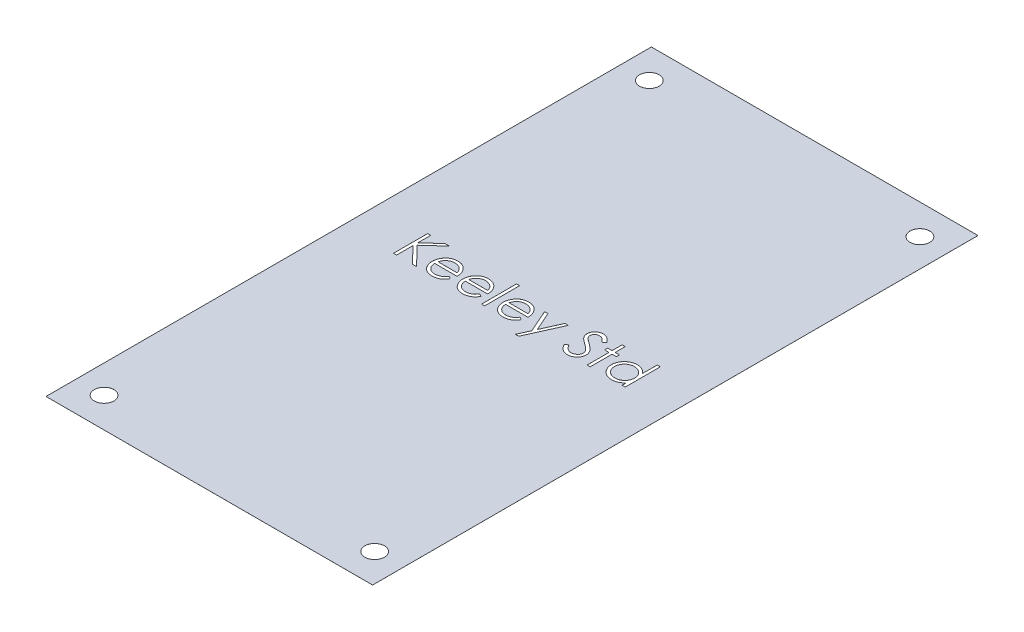
SolidWorks part; units mm, degrees
ref_plane "Front Plane" through (0, 0, 0) normal (0, 0, 1) x (1, 0, 0)
ref_plane "Top Plane" through (0, 0, 0) normal (0, 1, 0) x (1, 0, 0)
ref_plane "Right Plane" through (0, 0, 0) normal (1, 0, 0) x (0, 0, -1)
sketch "Sketch2" plane through (0, 0, 0) normal (0, 1, 0) x (1, 0, 0)
  line L1 (-30.353, -56.261) -> (30.353, -56.261)
  line L2 (-30.353, -56.261) -> (-30.353, 56.261)
  line L3 (-30.353, 56.261) -> (30.353, 56.261)
  line L4 (30.353, -56.261) -> (30.353, 56.261)
  line L5 (-30.353, -56.261) -> (30.353, 56.261) construction
  line L6 (-30.353, 56.261) -> (30.353, -56.261) construction
  point P0 (0, 0)
  dimension "D1" = 112.522
  dimension "D2" = 60.706
extrude "Boss-Extrude1" add sketch "Sketch2" along normal blind 0.0025
sketch "Sketch3" plane through (0, 0.0025, 0) normal (0, 1, 0) x (1, 0, 0)
  line L1 (-25.146, -50.673) -> (25.146, -50.673)
  line L2 (-25.146, -50.673) -> (-25.146, 50.673)
  line L3 (-25.146, 50.673) -> (25.146, 50.673)
  line L4 (25.146, -50.673) -> (25.146, 50.673)
  line L5 (-25.146, -50.673) -> (25.146, 50.673) construction
  line L6 (-25.146, 50.673) -> (25.146, -50.673) construction
  circle A0 centre (-25.146, 50.673) radius 1.8288
  circle A7 centre (25.146, 50.673) radius 1.8288
  circle A8 centre (25.146, -50.673) radius 1.8288
  circle A9 centre (-25.146, -50.673) radius 1.8288
  point P0 (0, 0)
  dimension "D3" = 3.6576
  dimension "D1" = 101.346
  dimension "D2" = 50.292
  dimension "D4" = 2
  dimension "D5" = 2
extrude "Cut-Extrude1" cut sketch "Sketch3" against normal through all contours A9 | A8 | A7 | A0
sketch "Sketch5" plane through (0, 0.0025, 0) normal (0, 1, 0) x (1, 0, 0)
  text T0 "Keeley Std\r\n\r\n" font "Century Gothic" height 6.35
extrude "Cut-Extrude2" cut sketch "Sketch5" against normal blind 2.54
